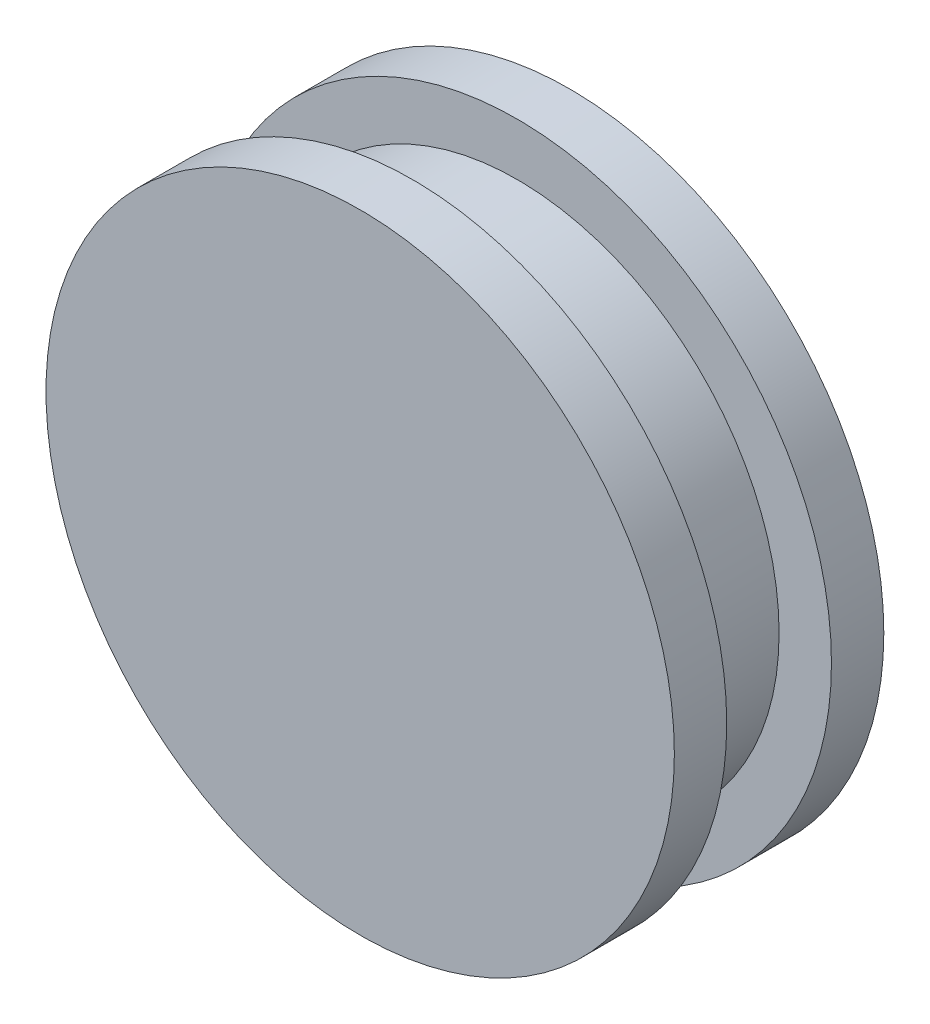
SolidWorks part; units mm, degrees
ref_plane "Front Plane" through (0, 0, 0) normal (0, 0, 1) x (1, 0, 0)
ref_plane "Top Plane" through (0, 0, 0) normal (0, 1, 0) x (1, 0, 0)
ref_plane "Right Plane" through (0, 0, 0) normal (1, 0, 0) x (0, 0, -1)
sketch "Sketch1" plane through (0, 0, 0) normal (0, 0, 1) x (1, 0, 0)
  circle A0 centre (0, 0) radius 300
  dimension "D1" = 600
extrude "Boss-Extrude1" add sketch "Sketch1" along normal blind 50
sketch "Sketch2" plane through (0, 0, 0) normal (0, 0, -1) x (-1, 0, 0)
  circle A0 centre (0, 0) radius 20
extrude "Cut-Extrude1" cut sketch "Sketch2" against normal blind 20
sketch "Sketch4" plane through (0, 0, 50) normal (0, 0, 1) x (1, 0, 0)
  circle A0 centre (0, 0) radius 250
  dimension "D1" = 500
extrude "Boss-Extrude2" add sketch "Sketch4" along normal blind 100
sketch "Sketch6" plane through (0, 0, 150) normal (0, 0, 1) x (1, 0, 0)
  circle A0 centre (0, 0) radius 300
extrude "Boss-Extrude3" add sketch "Sketch6" along normal blind 50
